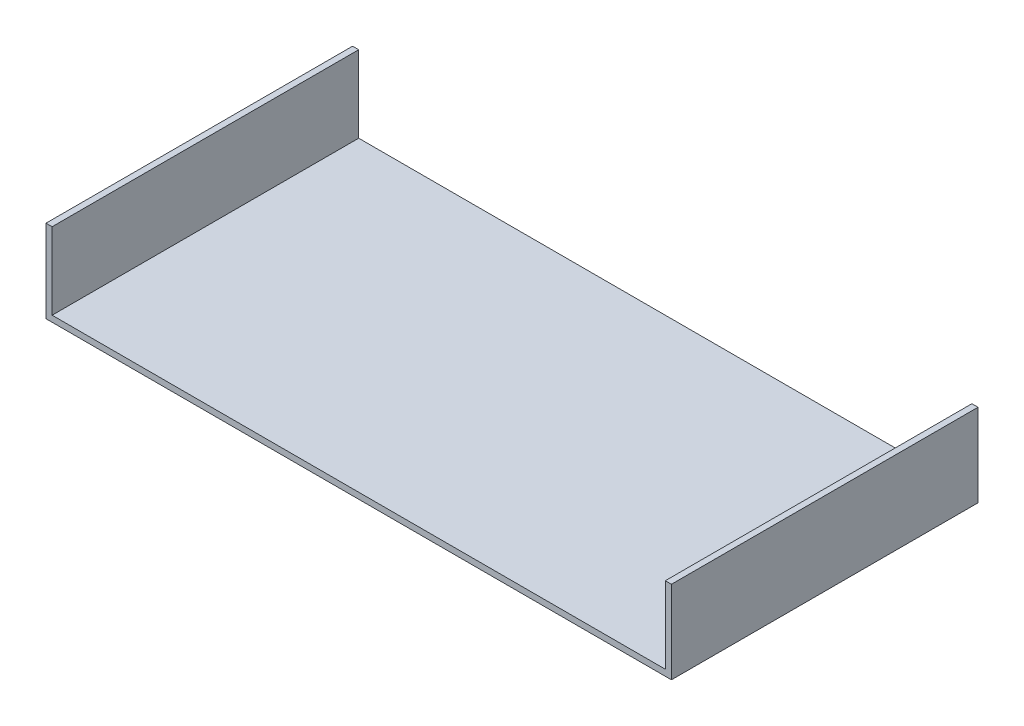
SolidWorks part; units mm, degrees
ref_plane "Front Plane" through (0, 0, 0) normal (0, 0, 1) x (1, 0, 0)
ref_plane "Top Plane" through (0, 0, 0) normal (0, 1, 0) x (1, 0, 0)
ref_plane "Right Plane" through (0, 0, 0) normal (1, 0, 0) x (0, 0, -1)
sketch "Sketch2" plane through (0, 0, 0) normal (0, 0, 1) x (1, 0, 0)
  line L0 (0, 0) -> (0, -2500)
  line L1 (0, -2500) -> (20000, -2500)
  line L2 (20000, -2500) -> (20000, 0)
  line L3 (-200, 0) -> (-200, -2700)
  line L4 (-200, -2700) -> (20200, -2700)
  line L5 (20200, -2700) -> (20200, 0)
  line L6 (-200, 0) -> (0, 0)
  line L7 (20000, 0) -> (20200, 0)
extrude "Boss-Extrude1" add sketch "Sketch2" against normal blind 10000
